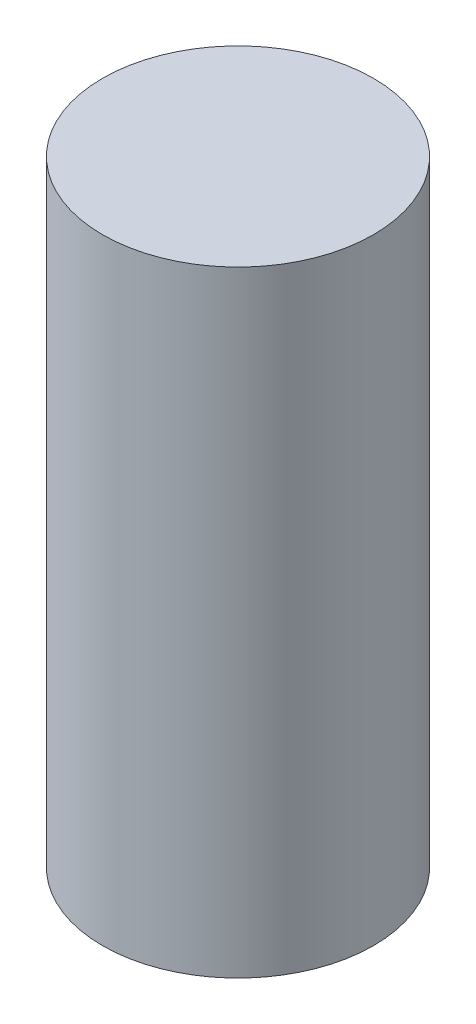
SolidWorks part; units mm, degrees
ref_plane "Ön Düzlem" through (0, 0, 0) normal (0, 0, 1) x (1, 0, 0)
ref_plane "Üst Düzlem" through (0, 0, 0) normal (0, 1, 0) x (1, 0, 0)
ref_plane "Sağ Düzlem" through (0, 0, 0) normal (1, 0, 0) x (0, 0, -1)
sketch "Çizim1" plane through (0, 0, 0) normal (0, 1, 0) x (1, 0, 0)
  circle A0 centre (0, 0) radius 11
  dimension "D1" = 22
extrude "Yükseklik-Ekstrüzyon1" add sketch "Çizim1" along normal blind 50
